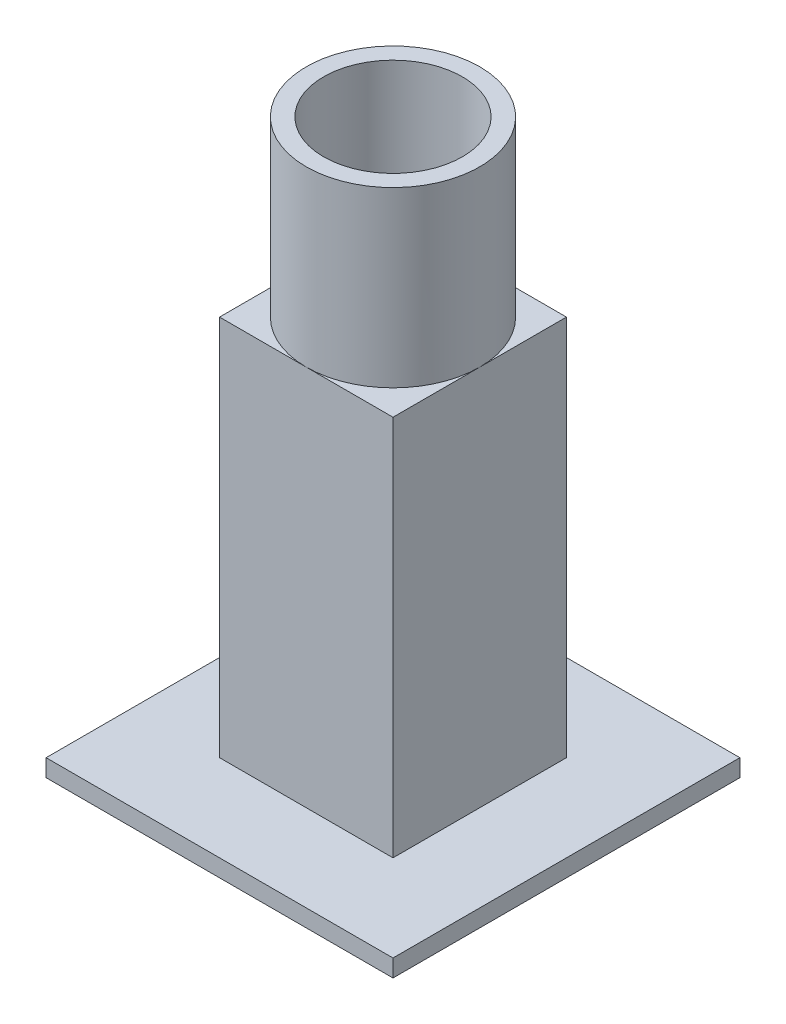
SolidWorks part; units mm, degrees
ref_plane "Front Plane" through (0, 0, 0) normal (0, 0, 1) x (1, 0, 0)
ref_plane "Top Plane" through (0, 0, 0) normal (0, 1, 0) x (1, 0, 0)
ref_plane "Right Plane" through (0, 0, 0) normal (1, 0, 0) x (0, 0, -1)
sketch "Sketch1" plane through (0, 0, 0) normal (0, 1, 0) x (1, 0, 0)
  line L1 (0, 0) -> (200, 0)
  line L2 (0, 0) -> (0, 200)
  line L3 (0, 200) -> (200, 200)
  line L4 (200, 0) -> (200, 200)
  dimension "D1" = 200
  dimension "D2" = 200
extrude "Boss-Extrude1" add sketch "Sketch1" along normal blind 10
sketch "Sketch2" plane through (0, 10, 0) normal (0, 1, 0) x (1, 0, 0)
  line L0 (0, 200) -> (0, 0) construction
  line L1 (50, 150) -> (150, 150)
  line L2 (50, 150) -> (50, 50)
  line L3 (50, 50) -> (150, 50)
  line L4 (150, 150) -> (150, 50)
  line L5 (0, 0) -> (200, 0) construction
  circle A0 centre (100, 100) radius 40
  dimension "D5" = 80
  dimension "D6" = 50
  dimension "D7" = 50
  dimension "D1" = 100
  dimension "D2" = 100
  dimension "D3" = 50
  dimension "D4" = 50
extrude "Boss-Extrude2" add sketch "Sketch2" along normal blind 220
sketch "Sketch3" plane through (0, 230, 0) normal (0, 1, 0) x (1, 0, 0)
  circle A0 centre (100, 100) radius 50
  circle A1 centre (100, 100) radius 40
  dimension "D1" = 100
extrude "Boss-Extrude3" add sketch "Sketch3" along normal blind 100
